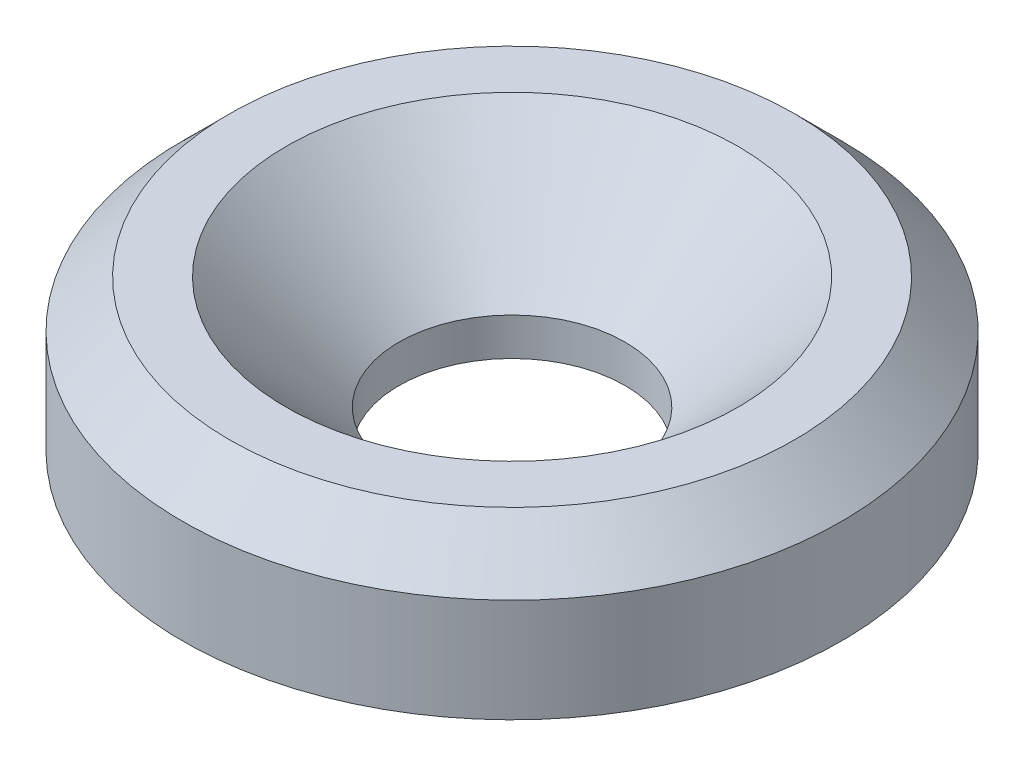
SolidWorks part; units mm, degrees
material "AISI 1020"
ref_plane "Front Plane" through (0, 0, 0) normal (0, 0, 1) x (1, 0, 0)
ref_plane "Top Plane" through (0, 0, 0) normal (0, 1, 0) x (1, 0, 0)
ref_plane "Right Plane" through (0, 0, 0) normal (1, 0, 0) x (0, 0, -1)
sketch "Sketch1" plane through (0, 0, 0) normal (0, 0, 1) x (1, 0, 0)
  line L0 (6, 0) -> (17.5, 0)
  line L1 (17.5, 0) -> (17.5, 5.5)
  line L2 (17.5, 5.5) -> (15, 8)
  line L3 (15, 8) -> (12, 8)
  line L4 (12, 8) -> (6, 2)
  line L5 (6, 2) -> (6, 0)
  line L6 (0, 0) -> (0, 8) construction
  point P3 (11.75, 0)
  dimension "D1" = 17.5
  dimension "6" = 6
  dimension "D2" = 5.5
  dimension "D3" = 8
  dimension "D4" = 135
  dimension "D5" = 45
  dimension "D6" = 2
revolve "Revolve1" add sketch "Sketch1" angle 360 about L6
